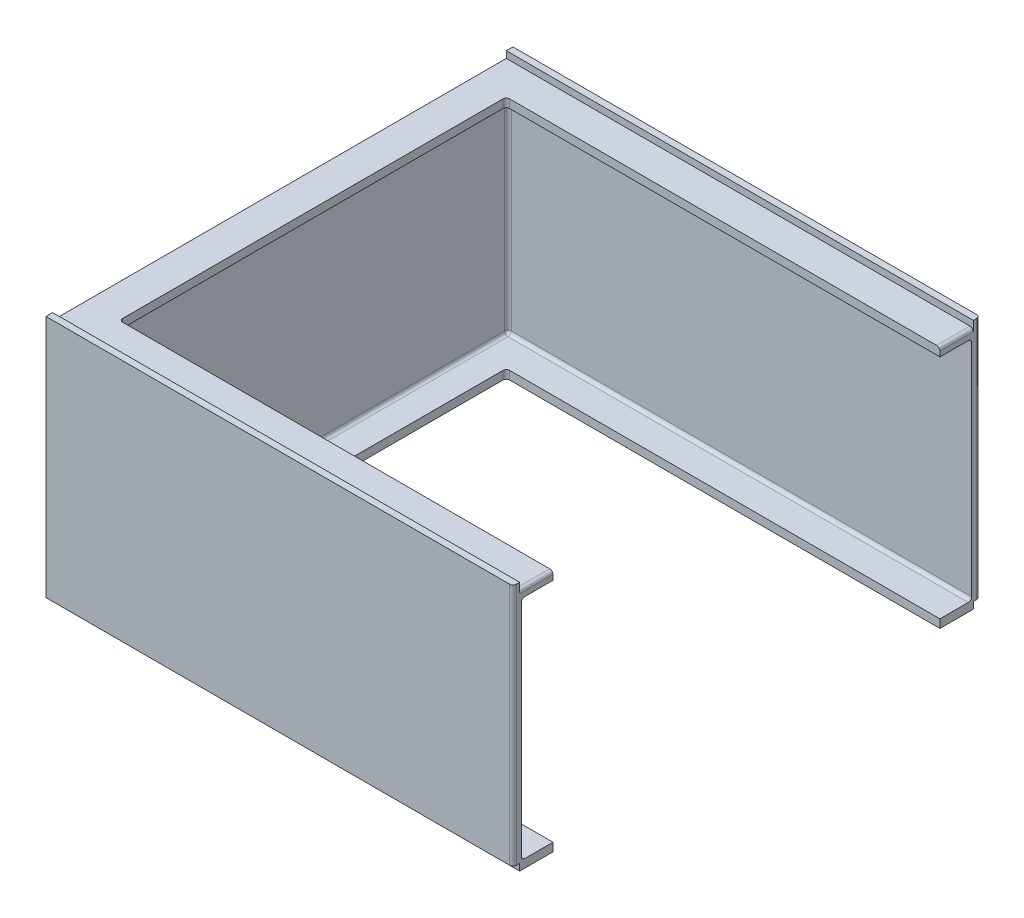
SolidWorks part; units mm, degrees
ref_plane "前视基准面" through (0, 0, 0) normal (0, 0, 1) x (1, 0, 0)
ref_plane "上视基准面" through (0, 0, 0) normal (0, 1, 0) x (1, 0, 0)
ref_plane "右视基准面" through (0, 0, 0) normal (1, 0, 0) x (0, 0, -1)
sketch "草图1" plane through (0, 0, 0) normal (0, 1, 0) x (1, 0, 0)
  line L1 (140, -140) -> (-140, -140)
  line L2 (140, -140) -> (140, 140)
  line L3 (140, 140) -> (-140, 140)
  line L4 (-140, -140) -> (-140, 140)
  line L5 (140, -140) -> (-140, 140) construction
  line L6 (140, 140) -> (-140, -140) construction
  point P0 (0, 0)
  dimension "D1" = 280
  dimension "D2" = 280
extrude "凸台-拉伸1" add sketch "草图1" along normal blind 150
sketch "草图2" plane through (0, 150, 0) normal (0, 1, 0) x (1, 0, 0)
  line L0 (140, -140) -> (140, 140) construction
  line L1 (140, 140) -> (-140, 140) construction
  line L5 (140, -136) -> (-140, -136)
  line L6 (140, -136) -> (140, 136)
  line L7 (140, 136) -> (-140, 136)
  line L8 (-140, -136) -> (-140, 136)
  line L9 (140, -136) -> (-140, 136) construction
  line L10 (140, 136) -> (-140, -136) construction
  point P0 (0, 0)
  dimension "D1" = 0
  dimension "D2" = 4
extrude "切除-拉伸1" cut sketch "草图2" against normal blind 4
sketch "草图3" plane through (0, 0, 0) normal (0, -1, 0) x (1, 0, 0)
  line L0 (-140, 136) -> (140, 136)
  line L1 (-140, -140) -> (-140, 140) construction
  line L2 (140, 140) -> (140, -140) construction
  line L3 (140, -140) -> (-140, -140) construction
  line L4 (-140, 140) -> (140, 140) construction
  line L5 (140, -140) -> (-140, -140)
  line L6 (140, 140) -> (140, 136)
  line L7 (-140, 140) -> (140, 140)
  line L8 (-140, -140) -> (-140, -136)
  line L9 (-140, -136) -> (140, -136)
  line L10 (-140, 136) -> (-140, 140)
  line L11 (140, -136) -> (140, -140)
  dimension "D1" = 4
  dimension "D2" = 4
extrude "切除-拉伸2" cut sketch "草图3" against normal blind 4
sketch "草图4" plane through (140, 0, 0) normal (1, 0, 0) x (0, 0, -1)
  line L0 (0, 146) -> (0, 0) construction
  line L1 (-136, 146) -> (136, 146) construction
  line L2 (-136, 0) -> (136, 0) construction
  line L6 (140, 150) -> (140, 4) construction
  line L7 (135, 5) -> (-135, 5)
  line L8 (135, 5) -> (135, 141)
  line L9 (135, 141) -> (-135, 141)
  line L10 (-135, 5) -> (-135, 141)
  line L11 (135, 5) -> (-135, 141) construction
  line L12 (135, 141) -> (-135, 5) construction
  point P6 (0, 73)
  point P8 (0, 73)
  dimension "D1" = 5
  dimension "D2" = 5
extrude "切除-拉伸3" cut sketch "草图4" against normal offset from surface (278 mm away) 2 up to face at (-140, 75.6667, 0)
sketch "草图6" plane through (0, 146, 0) normal (0, 1, 0) x (1, 0, 0)
  line L11 (140, -136) -> (140, 136) construction
  line L12 (140, 116) -> (-120, 116)
  line L14 (140, 116) -> (140, -116)
  line L15 (140, -116) -> (-120, -116)
  line L16 (-120, 116) -> (-120, -116)
  line L17 (140, 136) -> (-140, 136) construction
  line L18 (-140, -136) -> (140, -136) construction
  line L19 (-140, 136) -> (-140, -136) construction
  dimension "D1" = 20
  dimension "D2" = 20
  dimension "D3" = 20
extrude "切除-拉伸7" cut sketch "草图6" against normal through all
sketch "草图7" plane through (0, 0, 0) normal (1, 0, 0) x (0, 0, -1)
  line L0 (-135, 141) -> (-135, 5) construction
  line L1 (-135, 117) -> (-135, 113)
  line L2 (-135, 73) -> (135, 73) construction
  line L3 (135, 141) -> (135, 5) construction
  line L4 (0, 141) -> (0, 5) construction
  line L5 (-135, 141) -> (135, 141) construction
  line L6 (135, 5) -> (-135, 5) construction
  line L7 (-135, 117) -> (-134, 117)
  line L8 (-134, 117) -> (-134, 113)
  line L9 (-134, 113) -> (-135, 113)
  line L10 (-134, 33) -> (-135, 33)
  line L11 (-134, 29) -> (-134, 33)
  line L12 (-135, 29) -> (-134, 29)
  line L13 (-135, 29) -> (-135, 33)
  line L14 (135, 29) -> (135, 33)
  line L15 (135, 29) -> (134, 29)
  line L16 (134, 29) -> (134, 33)
  line L17 (134, 33) -> (135, 33)
  line L18 (134, 113) -> (135, 113)
  line L19 (134, 117) -> (134, 113)
  line L20 (135, 117) -> (134, 117)
  line L21 (135, 117) -> (135, 113)
  dimension "D1" = 1
  dimension "D2" = 4
  dimension "D3" = 40
fillet "圆角4" radius 2 2 edges at (140, 77, -140) (140, 77, 140)
fillet "圆角5" radius 2 2 edges at (140, 146, -126) (140, 146, 126)
fillet "圆角6" radius 2 4 edges at (-120, 2.5, 116) (-120, 2.5, -116) (-120, 143.5, -116) (-120, 143.5, 116)
fillet "圆角7" radius 2 8 edges at (-138, 73, -135) (-138, 73, 135) (-138, 141, 0) (-138, 5, 0) (1, 141, -135) (1, 5, -135) (1, 5, 135) (1, 141, 135)
